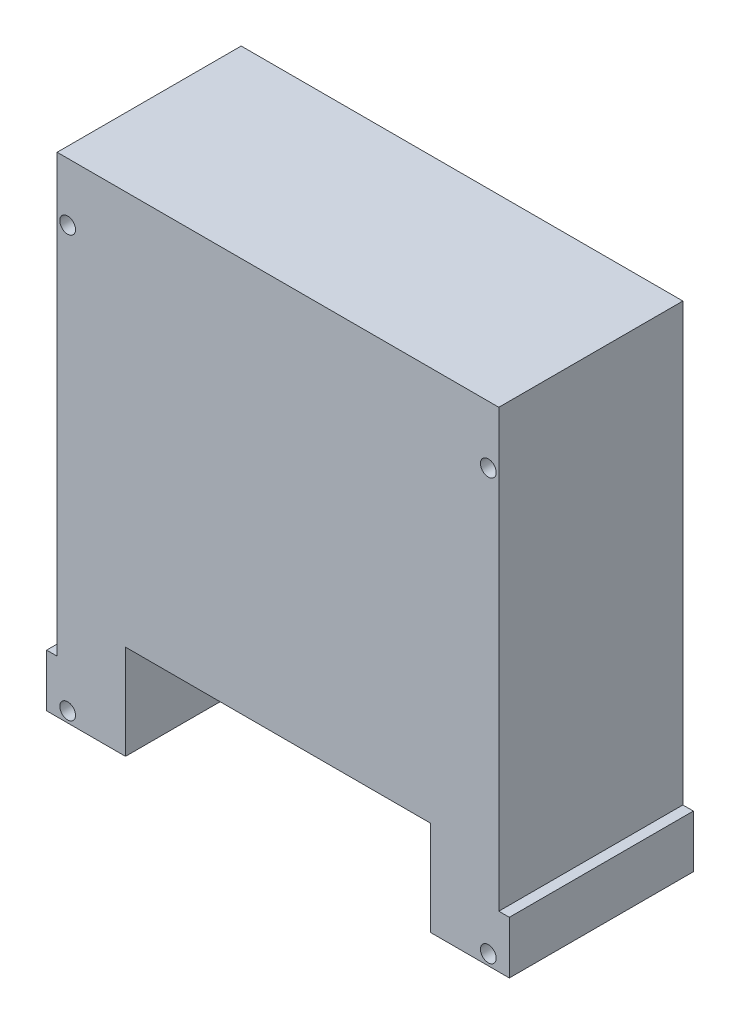
SolidWorks part; units mm, degrees
ref_plane "前视基准面" through (0, 0, 0) normal (0, 0, 1) x (1, 0, 0)
ref_plane "上视基准面" through (0, 0, 0) normal (0, 1, 0) x (1, 0, 0)
ref_plane "右视基准面" through (0, 0, 0) normal (1, 0, 0) x (0, 0, -1)
other "Configuration Table"
sketch "草图1" plane through (0, 0, 0) normal (0, 0, 1) x (1, 0, 0)
  line L0 (42, 93) -> (42, 0) construction
  line L1 (0, 0) -> (84, 0)
  line L2 (0, 0) -> (0, 93)
  line L3 (0, 93) -> (84, 93)
  line L4 (84, 0) -> (84, 93)
  line L5 (0, 46.5) -> (84, 46.5) construction
  dimension "D1" = 84
  dimension "D2" = 93
extrude "凸台-拉伸1" add sketch "草图1" along normal blind 35
sketch "草图2" plane through (0, 0, 35) normal (0, 0, 1) x (1, 0, 0)
  line L0 (42, 93) -> (42, 0) construction
  line L1 (84, 93) -> (0, 93) construction
  line L2 (0, 0) -> (84, 0) construction
  line L4 (2, 2) -> (82, 2) construction
  line L5 (2, 2) -> (2, 91) construction
  line L6 (2, 91) -> (82, 91) construction
  line L7 (82, 2) -> (82, 91) construction
  line L8 (2, 2) -> (82, 91) construction
  line L9 (2, 91) -> (82, 2) construction
  circle A2 centre (82, 2) radius 1.5
  circle A3 centre (2, 2) radius 1.5
  circle A4 centre (82, 82) radius 1.5
  circle A5 centre (2, 82) radius 1.5
  point P6 (42, 46.5)
  point P17 (0, 0)
  dimension "D3" = 3
  dimension "D1" = 80
  dimension "D2" = 89
  dimension "D4" = 80
extrude "切除-拉伸1" cut sketch "草图2" against normal up to next
sketch "草图3" plane through (0, 0, 35) normal (0, 0, 1) x (1, 0, 0)
  line L0 (0, 0) -> (84, 0) construction
  line L1 (13, 0) -> (71, 0)
  line L2 (13, 0) -> (13, 18)
  line L3 (13, 18) -> (71, 18)
  line L4 (71, 0) -> (71, 18)
  line L7 (42, 93) -> (42, 0) construction
  line L8 (84, 93) -> (0, 93) construction
  line L9 (42, 18) -> (42, 0) construction
  dimension "D1" = 18
  dimension "D2" = 58
extrude "切除-拉伸2" cut sketch "草图3" against normal up to next
ref_plane "基准面1" through (42, 0, 0) normal (1, 0, 0) x (0, 0, -1)
sketch "草图6" plane through (84, 0, 0) normal (1, 0, 0) x (0, 0, -1)
  line L0 (-35, 0) -> (-35, 93) construction
  line L1 (-35, 10) -> (0, 10)
  line L2 (-35, 10) -> (-35, 0)
  line L3 (-35, 0) -> (0, 0)
  line L4 (0, 10) -> (0, 0)
  dimension "D1" = 10
extrude "凸台-拉伸3" add sketch "草图6" along normal blind 2
mirror "镜向1" about plane through (42, 0, 0) normal (1, 0, 0) of "凸台-拉伸3"
